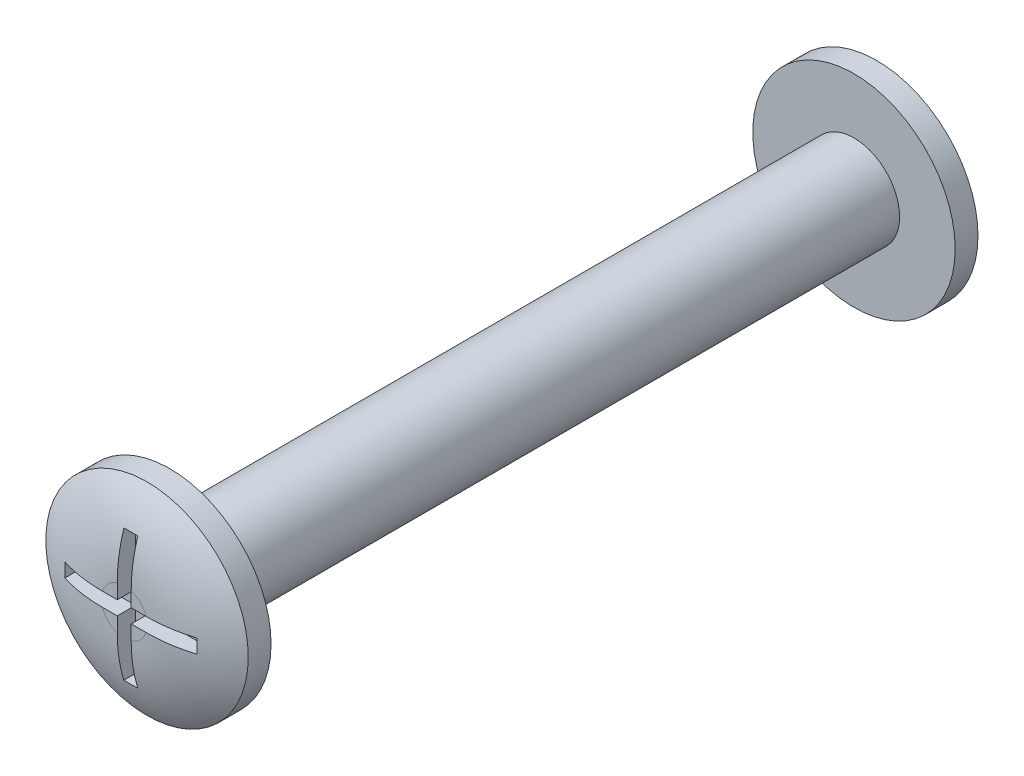
SolidWorks part; units mm, degrees
ref_plane "Front Plane" through (0, 0, 0) normal (0, 0, 1) x (1, 0, 0)
ref_plane "Top Plane" through (0, 0, 0) normal (0, 1, 0) x (1, 0, 0)
ref_plane "Right Plane" through (0, 0, 0) normal (1, 0, 0) x (0, 0, -1)
sketch "Sketch1" plane through (0, 0, 0) normal (0, 1, 0) x (1, 0, 0)
  line L0 (0, 0) -> (0, -3.175)
  line L1 (0, 47.625) -> (0, 50.8)
  line L2 (0, 0) -> (0, 47.625)
  line L3 (0, 47.625) -> (3.175, 47.625) construction
  line L4 (3.175, 47.625) -> (3.175, 0)
  line L5 (3.175, 0) -> (0, 0) construction
  line L6 (3.175, 0) -> (7.0459, 0)
  line L7 (3.175, 47.625) -> (7.0459, 47.625)
  line L8 (7.0459, 0) -> (7.0459, -1.5875)
  line L9 (0, -3.175) -> (1.5875, -3.175)
  line L12 (7.0459, 47.625) -> (7.0459, 49.2125)
  line L13 (0, 50.8) -> (1.5875, 50.8)
  arc A0 (7.0459, -1.5875) -> (1.5875, -3.175) centre (1.5875, 7.0027) cw
  arc A1 (1.5875, 50.8) -> (7.0459, 49.2125) centre (1.5875, 40.6223) cw
  dimension "D1" = 47.625
  dimension "D2" = 7.0459
  dimension "D3" = 1.5875
  dimension "D4" = 3.175
revolve "Revolve1" add sketch "Sketch1" angle 360 about L2
sketch "Sketch2" plane through (0, 0, 3.175) normal (0, 0, 1) x (1, 0, 0)
  line L1 (4.5932, -0.4856) -> (-4.5932, -0.4856)
  line L2 (4.5932, -0.4856) -> (4.5932, 0.4856)
  line L3 (4.5932, 0.4856) -> (-4.5932, 0.4856)
  line L4 (-4.5932, -0.4856) -> (-4.5932, 0.4856)
  line L5 (4.5932, -0.4856) -> (-4.5932, 0.4856) construction
  line L6 (4.5932, 0.4856) -> (-4.5932, -0.4856) construction
  line L7 (0.4856, 4.5932) -> (-0.4856, 4.5932)
  line L8 (0.4856, 4.5932) -> (0.4856, -4.5932)
  line L9 (0.4856, -4.5932) -> (-0.4856, -4.5932)
  line L10 (-0.4856, 4.5932) -> (-0.4856, -4.5932)
  line L11 (0.4856, 4.5932) -> (-0.4856, -4.5932) construction
  line L12 (0.4856, -4.5932) -> (-0.4856, 4.5932) construction
  point P0 (0, 0)
  point P6 (0, 0)
extrude "Cut-Extrude1" cut sketch "Sketch2" against normal blind 1.27 contours L3 L4 L1 L2 | L10 L9 L8 L7
ref_plane "Plane1" through (0, 0, -23.8125) normal (0, 0, -1) x (-1, 0, 0)
mirror "Mirror1" about plane through (0, 0, -23.8125) normal (0, 0, -1) of "Cut-Extrude1"
